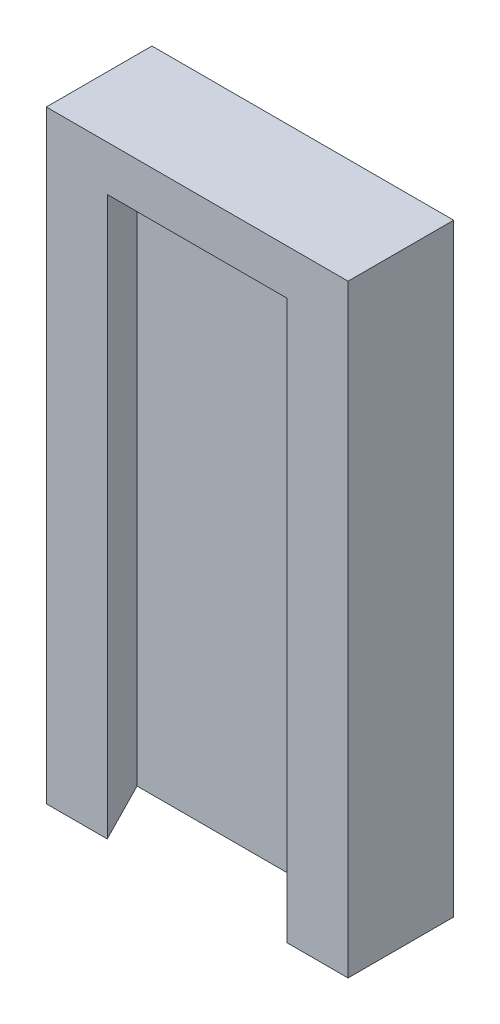
SolidWorks part; units mm, degrees
ref_plane "Front" through (0, 0, 0) normal (0, 0, 1) x (1, 0, 0)
ref_plane "Top" through (0, 0, 0) normal (0, 1, 0) x (1, 0, 0)
ref_plane "Right" through (0, 0, 0) normal (1, 0, 0) x (0, 0, -1)
sketch "Sketch1" plane through (0, 0, 0) normal (0, 1, 0) x (1, 0, 0)
  line L1 (-20, -7) -> (20, -7)
  line L2 (-20, -7) -> (-20, 7)
  line L3 (-20, 7) -> (20, 7)
  line L4 (20, -7) -> (20, 7)
  line L5 (-20, -7) -> (20, 7) construction
  line L6 (-20, 7) -> (20, -7) construction
  point P0 (0, 0)
  dimension "D1" = 40
  dimension "D2" = 14
extrude "Boss-Extrude1" add sketch "Sketch1" along normal mid plane 80
ref_plane "Plane1" through (0, 34, 0) normal (0, 1, 0) x (1, 0, 0)
sketch "Sketch3" plane through (0, 34, 0) normal (0, 1, 0) x (1, 0, 0)
  line L0 (-16.025, 1.05) -> (16.025, 1.05)
  line L1 (-20, -7) -> (20, -7) construction
  line L2 (-16.025, 1.05) -> (-11.9233, -7)
  line L3 (16.025, 1.05) -> (11.9233, -7)
  line L4 (-11.9233, -7) -> (11.9233, -7)
  point P2 (0, 1.05)
  dimension "D1" = 32.05
  dimension "D2" = 8.05
  dimension "D3" = 117
  dimension "D4" = 23.8466
extrude "Cut-Extrude1" cut sketch "Sketch3" against normal up to surface (74 mm away) up to face at (0, -40, 0)
